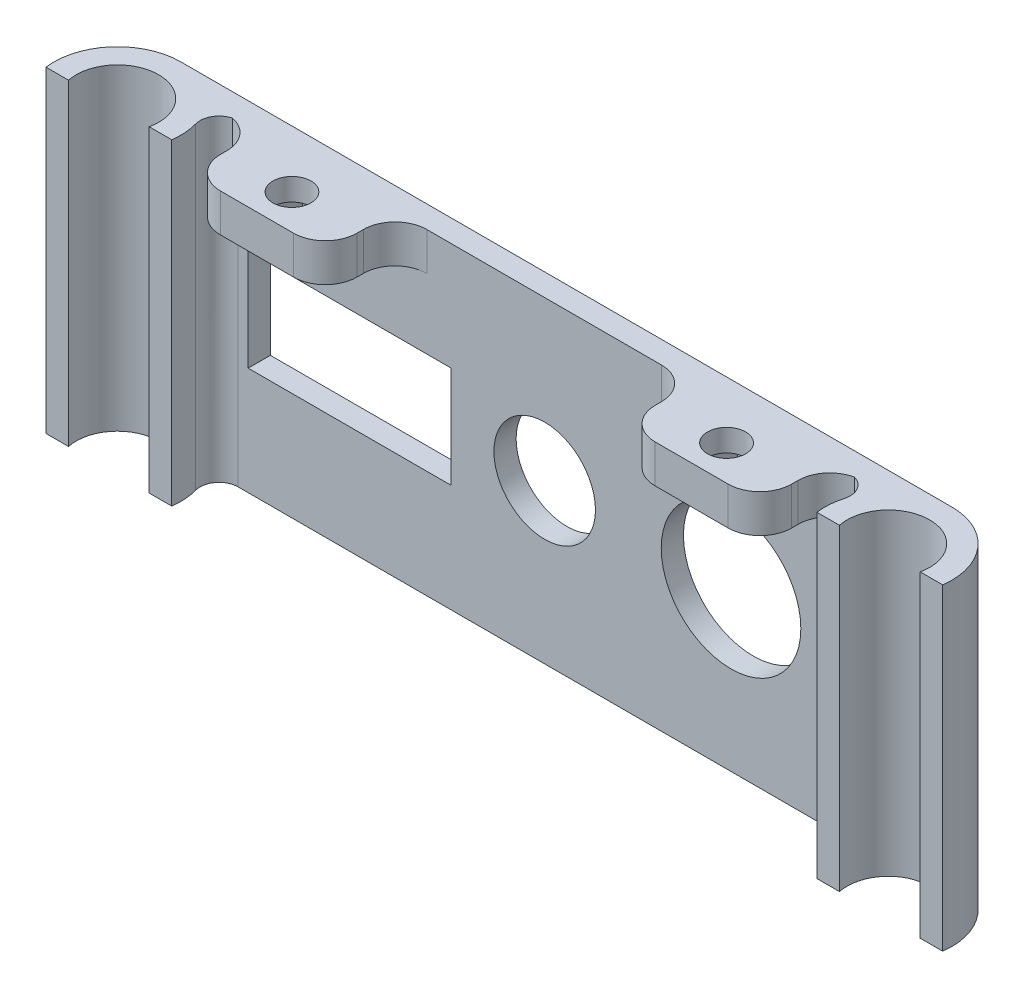
SolidWorks part; units mm, degrees
ref_plane "Front Plane" through (0, 0, 0) normal (0, 0, 1) x (1, 0, 0)
ref_plane "Top Plane" through (0, 0, 0) normal (0, 1, 0) x (1, 0, 0)
ref_plane "Right Plane" through (0, 0, 0) normal (1, 0, 0) x (0, 0, -1)
sketch "Sketch1" plane through (0, 0, 0) normal (0, 1, 0) x (1, 0, 0)
  line L0 (0, 0) -> (-121.5, 0)
  line L1 (-121.5, 10) -> (0, 10)
  line L2 (0, 10) -> (0, 6.5)
  line L3 (0, 6.5) -> (-121.5, 6.5)
  line L4 (-121.5, 0) -> (-121.5, -1.3505)
  line L5 (-121.5, -1.3505) -> (-137.3585, -1.3505)
  line L6 (-137.3585, -1.3505) -> (23.118, -1.3505)
  circle A0 centre (-121.5, 0) radius 6.5
  circle A1 centre (0, 0) radius 6.5
  circle A2 centre (-121.5, 0) radius 10
  circle A3 centre (0, 0) radius 10
extrude "Boss-Extrude2" add sketch "Sketch1" along normal blind 50 contours L6 A3 L2 A1 | L2 A3 L3 | A3 L1 A2 L3 | L3 A3 L0 A1 | L0 A3 L6 A1 | L0 A2 L3 A0 | L3 A2 L6 A0
sketch "Sketch2" plane through (0, 50, 0) normal (0, 1, 0) x (1, 0, 0)
  line L0 (-60.75, 6.5) -> (-60.75, -4.5)
  line L1 (-60.75, -4.5) -> (-105.75, -4.5)
  line L2 (-7.5993, 6.5) -> (-113.9007, 6.5) construction
  line L3 (-60.75, -4.5) -> (-15.75, -4.5)
  line L4 (-105.75, -4.5) -> (-105.75, 6.5)
  line L5 (-105.75, 6.5) -> (-15.75, 6.5)
  line L6 (-15.75, 6.5) -> (-15.75, -4.5)
  line L7 (-115, 0) -> (-95, 0)
  line L8 (-6.5, 0) -> (-26.5, 0)
  line L9 (-95, 6.5) -> (-95, -4.5)
  line L10 (-26.5, 6.5) -> (-26.5, -4.5)
  line L11 (-105.75, -4.5) -> (-95, -4.5)
  line L12 (-95, -4.5) -> (-84.25, -4.5)
  line L13 (-26.5, -4.5) -> (-37.25, -4.5)
  line L14 (-37.25, -4.5) -> (-37.25, 6.5)
  line L15 (-37.25, 6.5) -> (-84.25, 6.5)
  line L16 (-84.25, 6.5) -> (-84.25, -4.5)
  line L17 (-131.4084, -1.3505) -> (-107.8559, -1.3505)
  arc A0 (6.3582, -1.3505) -> (-6.3582, -1.3505) centre (0, 0) ccw construction
  circle A3 centre (-95, 1) radius 3
  circle A4 centre (-26.5, 1) radius 3
  circle A5 centre (-121.5, 0) radius 6.5
  circle A6 centre (-121.5, 0) radius 10
  line M14 (-115, 0) -> (-111.5, 0)
  line M16 (-113.9007, 6.5) -> (-7.5993, 6.5)
extrude "Boss-Extrude3" add sketch "Sketch2" against normal blind 6 contours A3 L9 L1 L16 L5 | A3 L7 L4 L1 L9 | A3 L9 L4 L7 M16 | A4 L10 L5 L14 L3 | A4 L8 L6 L5 L10 | A4 L10 L3 L6 L8 | L17 A6 A5 M14
sketch "Sketch3" plane through (0, 44, 0) normal (0, -1, 0) x (1, 0, 0)
  line L2 (-111.5916, 1.3505) -> (-115.1418, 1.3505)
  line L3 (-115, 0) -> (-111.5, 0)
  line L4 (-111.5916, 1.3505) -> (-115.1418, 1.3505)
  line L5 (-115, 0) -> (-111.5, 0)
  arc A2 (-115, 0) -> (-115.1418, 1.3505) centre (-121.5, 0) ccw
  arc A3 (-111.5, 0) -> (-111.5916, 1.3505) centre (-121.5, 0) ccw
  arc A4 (-115, 0) -> (-115.1418, 1.3505) centre (-121.5, 0) ccw
  arc A5 (-111.5, 0) -> (-111.5916, 1.3505) centre (-121.5, 0) ccw
  dimension "D1" = 0
extrude "Boss-Extrude4" add sketch "Sketch3" along normal up to surface (44 mm away) up to face at (-60.8146, 0, -3.7377)
fillet "Fillet1" radius 5 8 edges at (-105.75, 47, -6.5) (-84.25, 47, -6.5) (-37.25, 47, -6.5) (-15.75, 47, -6.5) (-15.75, 47, 4.5) (-37.25, 47, 4.5) (-84.25, 47, 4.5) (-105.75, 47, 4.5)
fillet "Fillet2" radius 3 2 edges at (-7.5993, 25, -6.5) (-113.9007, 25, -6.5)
sketch "Sketch5" plane through (0, 44, 0) normal (0, -1, 0) x (1, 0, 0)
  line L1 (-21.8969, -1) -> (-24.1984, 2.9864)
  line L2 (-24.1984, 2.9864) -> (-28.8016, 2.9864)
  line L3 (-28.8016, 2.9864) -> (-31.1031, -1)
  line L4 (-31.1031, -1) -> (-28.8016, -4.9864)
  line L5 (-28.8016, -4.9864) -> (-24.1984, -4.9864)
  line L6 (-24.1984, -4.9864) -> (-21.8969, -1)
  line L7 (-90.4012, -1) -> (-92.7006, 2.9827)
  line L8 (-92.7006, 2.9827) -> (-97.2994, 2.9827)
  line L9 (-97.2994, 2.9827) -> (-99.5988, -1)
  line L10 (-99.5988, -1) -> (-97.2994, -4.9827)
  line L11 (-97.2994, -4.9827) -> (-92.7006, -4.9827)
  line L12 (-92.7006, -4.9827) -> (-90.4012, -1)
  circle A2 centre (-26.5, -1) radius 3.9864 construction
  circle A3 centre (-95, -1) radius 3.9827 construction
extrude "Cut-Extrude3" cut sketch "Sketch5" against normal blind 2.5
sketch "Sketch6" plane through (0, 0, -10) normal (0, 0, -1) x (-1, 0, 0)
  line L0 (0, 25) -> (121.5, 25)
  line L1 (75.3965, 17) -> (107.3965, 17)
  line L2 (75.3965, 17) -> (75.3965, 33)
  line L3 (75.3965, 33) -> (107.3965, 33)
  line L4 (107.3965, 17) -> (107.3965, 33)
  line L5 (0, 50) -> (0, 0) construction
  line L6 (121.5, 50) -> (121.5, 0) construction
  line L7 (107.3965, 33) -> (107.3965, 17)
  line L8 (75.3965, 17) -> (75.3965, 0)
  line L9 (121.5, 0) -> (0, 0) construction
  circle A0 centre (31.3011, 25) radius 11
  circle A1 centre (60.6669, 25) radius 8
  circle A2 centre (31.3011, 25) radius 16
  circle A3 centre (60.6669, 25) radius 9
extrude "Cut-Extrude4" cut sketch "Sketch6" against normal blind 10 contours L1 L4 L0 L2 | L0 L4 L3 L2 | L0 A1 | L0 A1 | L0 A0 | L0 A0
